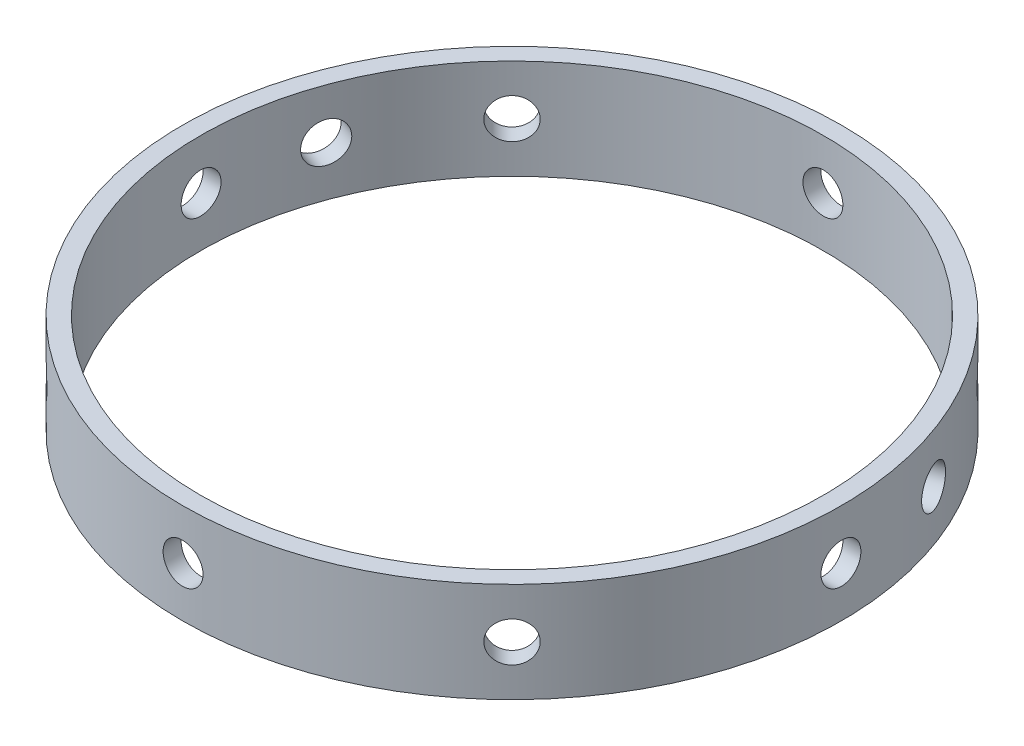
SolidWorks part; units mm, degrees
ref_plane "Front Plane" through (0, 0, 0) normal (0, 0, 1) x (1, 0, 0)
ref_plane "Top Plane" through (0, 0, 0) normal (0, 1, 0) x (1, 0, 0)
ref_plane "Right Plane" through (0, 0, 0) normal (1, 0, 0) x (0, 0, -1)
sketch "Sketch1" plane through (0, 0, 0) normal (0, 1, 0) x (1, 0, 0)
  circle A0 centre (0, 0) radius 39.624
  circle A1 centre (0, 0) radius 41.91
  circle A2 centre (0, 0) radius 41.91
  point P23 (0, 0)
  point P24 (0, 0)
  point P28 (0, 0)
  point P50 (0, 0)
extrude "Boss-Extrude2" add sketch "Sketch1" along normal blind 12.7 contours A1 A0
sketch "Sketch2" plane through (0, 0, 0) normal (0, 0, 1) x (1, 0, 0)
  circle A1 centre (0, 6.35) radius 2.54
extrude "Cut-Extrude1" cut sketch "Sketch2" against normal blind 56.7
pattern_circular "CirPattern1" count 8 over 360 about axis through (0, 12.7, 0) along (0, 1, 0) of "Cut-Extrude1"
pattern_circular "CirPattern2" count 2 over 70 about axis through (0, 12.7, 0) along (0, 1, 0) of "Cut-Extrude1"
